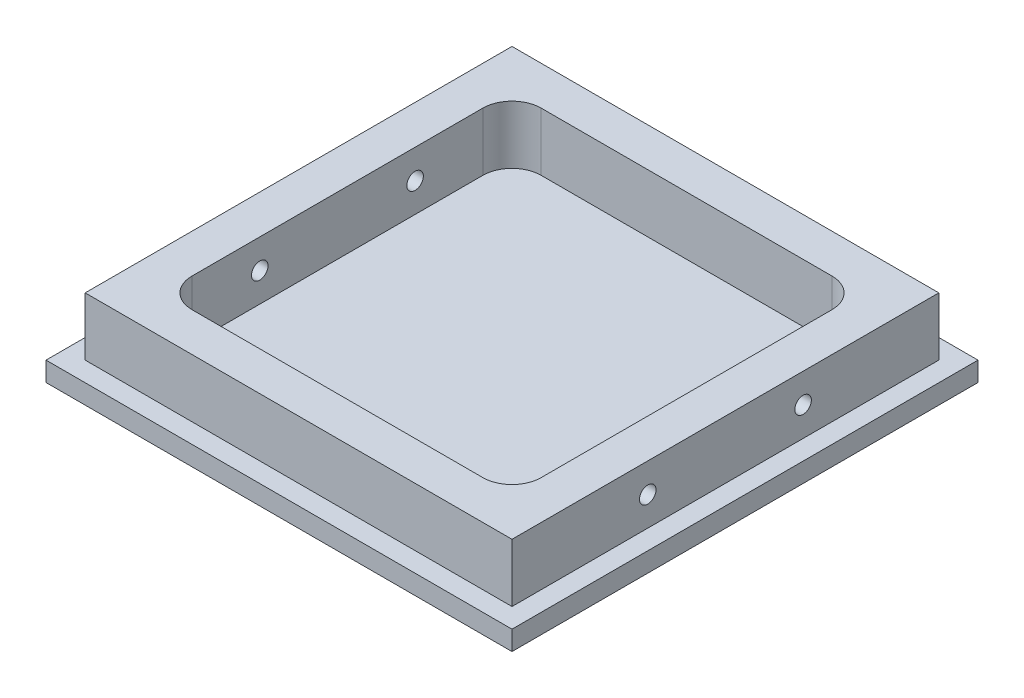
SolidWorks part; units mm, degrees
material "6061-T6 (SS)"
ref_plane "Front Plane" through (0, 0, 0) normal (0, 0, 1) x (1, 0, 0)
ref_plane "Top Plane" through (0, 0, 0) normal (0, 1, 0) x (1, 0, 0)
ref_plane "Right Plane" through (0, 0, 0) normal (1, 0, 0) x (0, 0, -1)
sketch "Sketch1" plane through (0, 0, 0) normal (0, 1, 0) x (1, 0, 0)
  line L1 (-38.1, -38.1) -> (38.1, -38.1)
  line L2 (-38.1, -38.1) -> (-38.1, 38.1)
  line L3 (-38.1, 38.1) -> (38.1, 38.1)
  line L4 (38.1, -38.1) -> (38.1, 38.1)
  line L5 (-38.1, -38.1) -> (38.1, 38.1) construction
  line L6 (-38.1, 38.1) -> (38.1, -38.1) construction
  point P0 (0, 0)
  dimension "D1" = 76.2
  dimension "D2" = 76.2
extrude "Boss-Extrude1" add sketch "Sketch1" along normal blind 3.175
sketch "Sketch2" plane through (0, 3.175, 0) normal (0, 1, 0) x (1, 0, 0)
  line L0 (-38.1, 38.1) -> (-38.1, -38.1) construction
  line L1 (34.8971, -34.8971) -> (-34.8971, -34.8971)
  line L2 (34.8971, -34.8971) -> (34.8971, 34.8971)
  line L3 (34.8971, 34.8971) -> (-34.8971, 34.8971)
  line L4 (-34.8971, -34.8971) -> (-34.8971, 34.8971)
  line L5 (34.8971, -34.8971) -> (-34.8971, 34.8971) construction
  line L6 (34.8971, 34.8971) -> (-34.8971, -34.8971) construction
  line L7 (28.5471, -28.5471) -> (-28.5471, -28.5471)
  line L8 (28.5471, -28.5471) -> (28.5471, 28.5471)
  line L9 (28.5471, 28.5471) -> (-28.5471, 28.5471)
  line L10 (-28.5471, -28.5471) -> (-28.5471, 28.5471)
  line L11 (28.5471, -28.5471) -> (-28.5471, 28.5471) construction
  line L12 (28.5471, 28.5471) -> (-28.5471, -28.5471) construction
  line L14 (38.1, 38.1) -> (-38.1, 38.1) construction
  point P0 (0, 0)
  point P6 (0, 0)
  dimension "D1" = 3.2029
  dimension "D2" = 3.2029
  dimension "D3" = 6.35
extrude "Boss-Extrude2" add sketch "Sketch2" along normal blind 9.525 contours L10 L9 L8 L7
fillet "Fillet1" radius 4.7625 4 edges at (-28.5471, 7.9375, 28.5471) (28.5471, 7.9375, 28.5471) (28.5471, 7.9375, -28.5471) (-28.5471, 7.9375, -28.5471)
sketch "Sketch8" plane through (34.8971, 0, 0) normal (1, 0, 0) x (0, 0, -1)
  line L0 (-38.1, 3.175) -> (38.1, 3.175) construction
  point P0 (-12.7, 7.9375)
  dimension "D1" = 4.7625
  dimension "D2" = 12.7
hole_wizard "#6-32 Tapped Hole2" positions "Sketch10" profile "Sketch9" tap size "#6-32" standard "ANSI Inch"
sketch "Sketch10" plane through (34.8971, 0, 0) normal (1, 0, 0) x (0, 0, -1)
  point P0 (-12.7, 7.9375)
cosmetic thread "Hole Thread1" parameters "D1"=4.7346, "D2"=3.5052
sketch "Sketch9" plane through (34.8971, 7.9375, 12.7) normal (0, 1, 0) x (0, 0, -1)
  line L0 (0, 0) -> (0, 11.9887)
  line L1 (0, 11.9887) -> (1.3525, 11.176)
  line L2 (1.3525, 11.176) -> (1.3525, 0)
  line L5 (1.3525, 0) -> (0, 0)
  line L10 (0, 11.9887) -> (-1.3526, 11.176) construction
  line L11 (0, -6.35) -> (0, 107.95) construction
  dimension "Tap Drill Dia." = 2.7051
  dimension "Tap Drill Depth" = 11.176
  dimension "Drill Angle" = 118
mirror "Mirror1" about plane through (0, 0, 0) normal (0, 0, 1) of "#6-32 Tapped Hole2"
mirror "Mirror2" about plane through (0, 0, 0) normal (1, 0, 0) of "Mirror1", "#6-32 Tapped Hole2"
sketch "Sketch12" plane through (0, 12.7, 0) normal (0, 1, 0) x (1, 0, 0)
  line L0 (38.1, -38.1) -> (38.1, 38.1) construction
  point P0 (31.75, 28.575)
  point P1 (31.75, 0)
  point P2 (31.75, -28.575)
  dimension "D1" = 28.575
  dimension "D2" = 28.575
  dimension "D3" = 6.35
equation "\"D2@Sketch2\"=\"D1@Sketch2\""
equation "\"D2@Sketch1\"=\"D1@Sketch1\""
